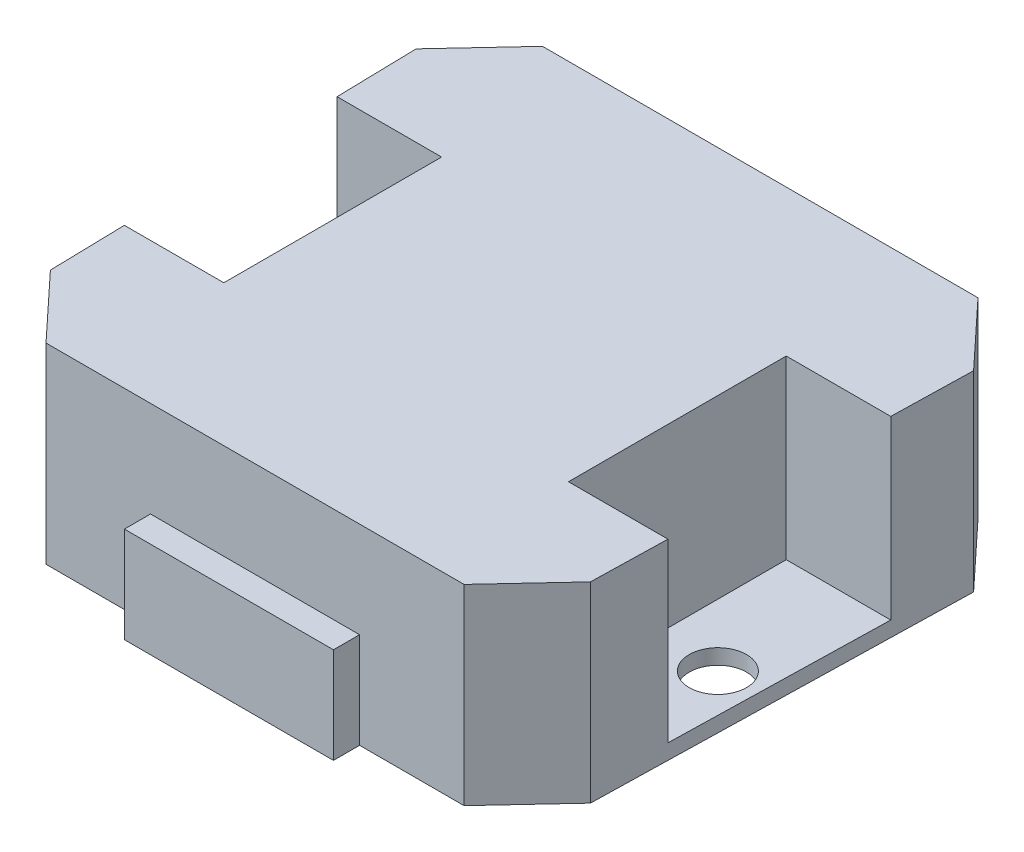
SolidWorks part; units mm, degrees
ref_plane "Front Plane" through (0, 0, 0) normal (0, 0, 1) x (1, 0, 0)
ref_plane "Top Plane" through (0, 0, 0) normal (0, 1, 0) x (1, 0, 0)
ref_plane "Right Plane" through (0, 0, 0) normal (1, 0, 0) x (0, 0, -1)
sketch "Sketch1" plane through (0, 0, 0) normal (0, 1, 0) x (1, 0, 0)
  line L0 (-31, -21.4942) -> (31, -21.4942) construction
  line L1 (24, -29) -> (-24, -29)
  line L2 (-24, -29) -> (-31, -21.4942)
  line L3 (-31, -21.4942) -> (-32, 21.4942)
  line L4 (-32, 21.4942) -> (-25, 29)
  line L5 (-25, 29) -> (25, 29)
  line L6 (25, 29) -> (32, 21.4942)
  line L7 (0, 29) -> (0, -29) construction
  line L8 (32, 21.4942) -> (31, -21.4942)
  line L9 (31, -21.4942) -> (24, -29)
  line L10 (-32, 21.4942) -> (32, 21.4942) construction
  line L11 (-26.9336, -2.8) -> (-31.4324, -2.9047) construction
  line L12 (26.9336, -2.8) -> (31.4324, -2.9047) construction
  circle A0 centre (-26.9336, -2.8) radius 3.29
  circle A1 centre (26.9336, -2.8) radius 3.29
  point P0 (0, 0)
  point P14 (0, 29)
  point P19 (0, -29)
  dimension "D3" = 6.58
  dimension "D1" = 64
  dimension "D2" = 62
  dimension "D4" = 43
  dimension "D5" = 50
  dimension "D6" = 48
  dimension "D7" = 58
  dimension "D8" = 26.2
  dimension "D9" = 4.5
extrude "Boss-Extrude1" add sketch "Sketch1" along normal blind 22
sketch "Sketch2" plane through (0, 0, 29) normal (0, 0, 1) x (1, 0, 0)
  line L0 (-24, 0) -> (24, 0) construction
  line L1 (-12, 0) -> (12, 0)
  line L2 (-12, 0) -> (-12, 11)
  line L3 (-12, 11) -> (12, 11)
  line L4 (12, 0) -> (12, 11)
  point P6 (0, 11)
  dimension "D1" = 24
  dimension "D2" = 11
extrude "Boss-Extrude2" add sketch "Sketch2" along normal blind 3
sketch "Sketch3" plane through (0, 22, 0) normal (0, 1, 0) x (1, 0, 0)
  line L0 (-24, -29) -> (24, -29) construction
  line L1 (-19.7838, 29) -> (19.7838, 29) construction
  line L2 (-19.7838, 29) -> (-19.7838, -29) construction
  line L3 (-19.7838, -29) -> (19.7838, -29) construction
  line L4 (19.7838, 29) -> (19.7838, -29) construction
  line L5 (-19.7838, 29) -> (19.7838, -29) construction
  line L6 (-19.7838, -29) -> (19.7838, 29) construction
  line L7 (-32, 21.4942) -> (-31, -21.4942) construction
  line L8 (-19.7838, 12.2) -> (-31.7838, 12.2)
  line L9 (-19.7838, 12.2) -> (-19.7838, -12.8)
  line L10 (-19.7838, -12.8) -> (-31.7838, -12.8)
  line L11 (-31.7838, 12.2) -> (-31.7838, -12.8)
  line L12 (31, -21.4942) -> (32, 21.4942) construction
  line L13 (19.7838, 12.2) -> (31.7838, 12.2)
  line L14 (19.7838, 12.2) -> (19.7838, -12.8)
  line L15 (19.7838, -12.8) -> (31.7838, -12.8)
  line L16 (31.7838, 12.2) -> (31.7838, -12.8)
  circle A0 centre (-26.9336, -2.8) radius 3.29 construction
  circle A1 centre (26.9336, -2.8) radius 3.29 construction
  circle A2 centre (-26.9336, -2.8) radius 3.29 construction
  circle A3 centre (26.9336, -2.8) radius 3.29 construction
  point P0 (0, 0)
  dimension "D1" = 10
  dimension "D2" = 15
  dimension "D3" = 12
extrude "Cut-Extrude1" cut sketch "Sketch3" against normal offset from surface (20.25 mm away) 1.75 up to face at (-26.9336, 0, 6.09)
sketch "Sketch4" plane through (0, 0, 0) normal (0, -1, 0) x (1, 0, 0)
  circle A0 centre (0, 0) radius 1.5 construction
  dimension "D1" = 3
